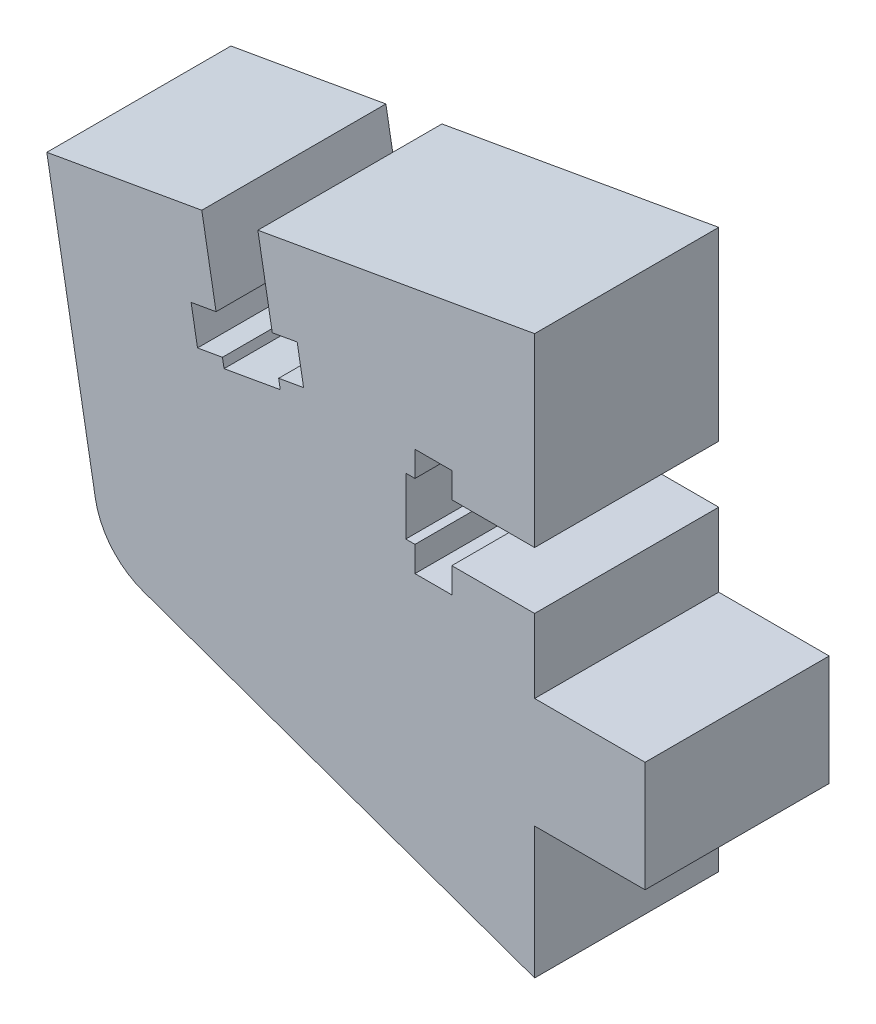
SolidWorks part; units mm, degrees
ref_plane "Płaszczyzna przednia" through (0, 0, 0) normal (0, 0, 1) x (1, 0, 0)
ref_plane "Płaszczyzna górna" through (0, 0, 0) normal (0, 1, 0) x (1, 0, 0)
ref_plane "Płaszczyzna prawa" through (0, 0, 0) normal (1, 0, 0) x (0, 0, -1)
sketch "Szkic1" plane through (0, 0, 0) normal (0, 0, 1) x (1, 0, 0)
  line L0 (269.0165, -406.8685) -> (271.6543, -421.828)
  line L2 (280.4807, -404.8015) -> (295.5147, -402.1506)
  line L5 (295.5147, -432.4628) -> (274.2533, -424.9023)
  line L6 (301.5147, -425.3139) -> (301.5147, -419.3139)
  line L8 (295.5147, -402.1506) -> (295.5147, -412.2139)
  line L9 (295.5147, -419.3139) -> (301.5147, -419.3139)
  line L10 (269.0165, -406.8685) -> (277.4355, -405.384)
  line L11 (289.0147, -412.2139) -> (288.5147, -412.2139)
  line L12 (295.5147, -412.2139) -> (291.0147, -412.2139)
  line L13 (295.5147, -415.3139) -> (291.0147, -415.3139)
  line L14 (288.5147, -412.2139) -> (288.5147, -415.3139)
  line L15 (295.5147, -415.3139) -> (295.5147, -419.3139)
  line L16 (289.0147, -410.8389) -> (291.0147, -410.8389)
  line L17 (289.0147, -410.8389) -> (289.0147, -412.2139)
  line L18 (289.0147, -416.6889) -> (291.0147, -416.6889)
  line L19 (291.0147, -410.8389) -> (291.0147, -412.2139)
  line L20 (289.0147, -415.3139) -> (289.0147, -416.6889)
  line L21 (291.0147, -415.3139) -> (291.0147, -416.6889)
  line L22 (289.0147, -415.3139) -> (288.5147, -415.3139)
  line L24 (277.4355, -405.384) -> (278.2092, -409.7714)
  line L28 (280.4807, -404.8015) -> (281.2621, -409.2331)
  line L29 (295.5147, -432.4628) -> (295.5147, -425.3139)
  line L30 (278.6433, -412.2335) -> (281.6962, -411.6951)
  line L31 (276.8551, -410.0102) -> (278.2092, -409.7714)
  line L32 (276.8551, -410.0102) -> (277.2024, -411.9798)
  line L33 (282.6162, -408.9944) -> (282.9635, -410.964)
  line L34 (277.2024, -411.9798) -> (278.5565, -411.7411)
  line L35 (278.5565, -411.7411) -> (278.6433, -412.2335)
  line L36 (281.6094, -411.2027) -> (281.6962, -411.6951)
  line L37 (281.2621, -409.2331) -> (282.6162, -408.9944)
  line L38 (281.6094, -411.2027) -> (282.9635, -410.964)
  line L40 (295.5147, -425.3139) -> (301.5147, -425.3139)
  arc A0 (274.2533, -424.9023) -> (271.6543, -421.828) centre (275.5935, -421.1335) cw
  point P1 (-279.7536, -416.222)
  point P5 (296.1513, -406.546)
  point P8 (270.1506, -423.3158)
  point P12 (-294.9836, -418.9075)
  point P25 (-306.4815, -416.8731)
  point P27 (-292.8907, -418.5384)
  point P28 (-311.5788, -421.8336)
  point P29 (-294.2022, -423.3391)
  point P30 (-278.9722, -420.6536)
  point P31 (267.2202, -407.6474)
  point P32 (-270.0818, -410.4549)
  point P33 (298.2351, -418.3637)
  dimension "D9" = 0
  dimension "D10" = 0.5
  dimension "D11" = 2
  dimension "D12" = 5.85
  dimension "D13" = 7
  dimension "D15" = 1.375
  dimension "D19" = 7
  dimension "D16" = 0
  dimension "D17" = 6
  dimension "D7" = 4
  dimension "D2" = 3.1
  dimension "D3" = 1.375
  dimension "D4" = 5.85
  dimension "D5" = 0.5
  dimension "D6" = 2
  dimension "D8" = 6
  dimension "D14" = 4
  dimension "D18" = 3.1
extrude "Dodanie-wyciągnięcie1" add sketch "Szkic1" along normal blind 10
equation "\"tolerancja_wpusy\"=0.2"
equation "\"dlugosc_wpustu_duzy\"=20"
equation "\"srednica_otworu_M3\"=3.1"
equation "\"szerokosc_nogi_T\"=3.1"
equation "\"dlugosc_T_30\"=11"
equation "\"grubosc_na_nakretke_kwadrat\"=2"
equation "\"szerokosc_na_nakretke_kwadrat\"=5.85"
equation "\"wyokosc_nadstawki_T\"=0.5"
equation "\"dlugosc_T_20_6\"=14"
equation "\"D2@Szkic1\"=\"srednica_otworu_M3\""
equation "\"D3@Szkic1\"=(\"szerokosc_na_nakretke_kwadrat\"-\"szerokosc_nogi_T\")/2"
equation "\"D4@Szkic1\"=\"szerokosc_na_nakretke_kwadrat\""
equation "\"D5@Szkic1\"=\"wyokosc_nadstawki_T\""
equation "\"D6@Szkic1\"=\"grubosc_na_nakretke_kwadrat\""
equation "\"D10@Szkic1\"=\"wyokosc_nadstawki_T\""
equation "\"D11@Szkic1\"=\"grubosc_na_nakretke_kwadrat\""
equation "\"D12@Szkic1\"=\"szerokosc_na_nakretke_kwadrat\""
equation "\"D15@Szkic1\"=(\"szerokosc_na_nakretke_kwadrat\"-\"szerokosc_nogi_T\")/2"
equation "\"D18@Szkic1\"=\"szerokosc_nogi_T\""
